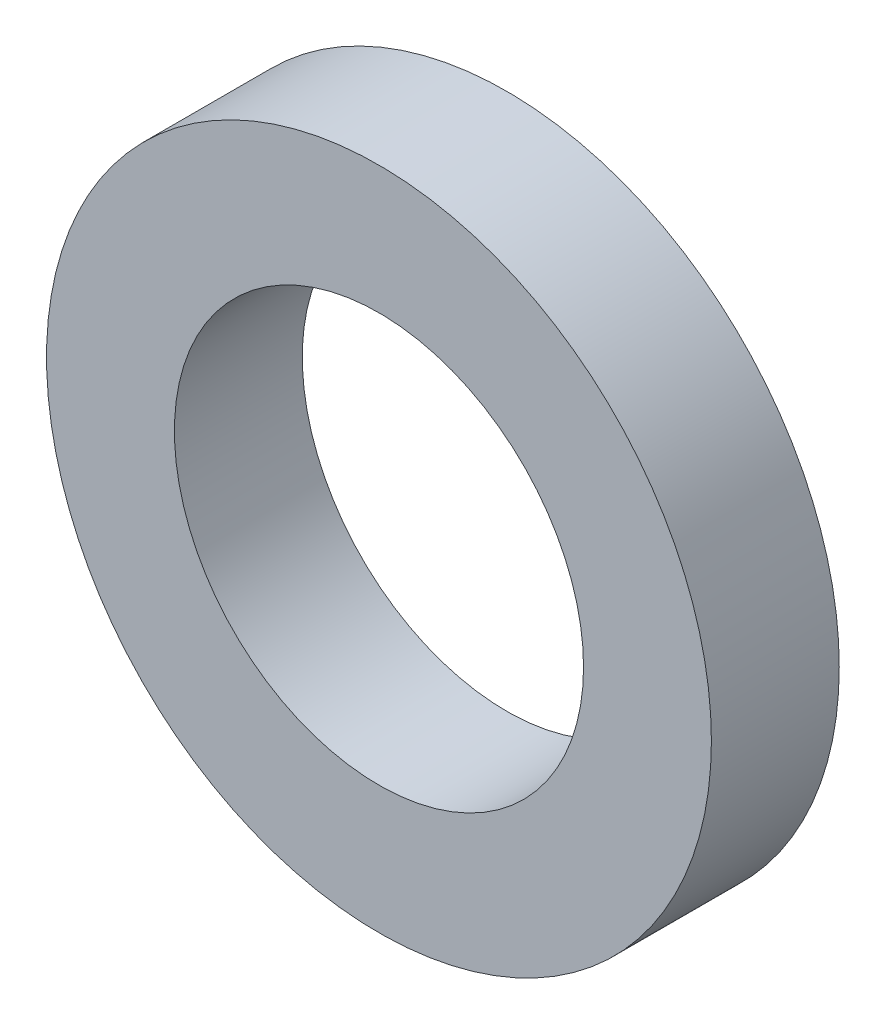
SolidWorks part; units mm, degrees
ref_plane "Front Plane" through (0, 0, 0) normal (0, 0, 1) x (1, 0, 0)
ref_plane "Top Plane" through (0, 0, 0) normal (0, 1, 0) x (1, 0, 0)
ref_plane "Right Plane" through (0, 0, 0) normal (1, 0, 0) x (0, 0, -1)
sketch "Sketch1" plane through (0, 0, 0) normal (0, 0, 1) x (1, 0, 0)
  circle A0 centre (0, 0) radius 1.6
  circle A1 centre (0, 0) radius 2.6
  dimension "D1" = 3.2
  dimension "D2" = 1
extrude "Boss-Extrude1" add sketch "Sketch1" along normal blind 1
